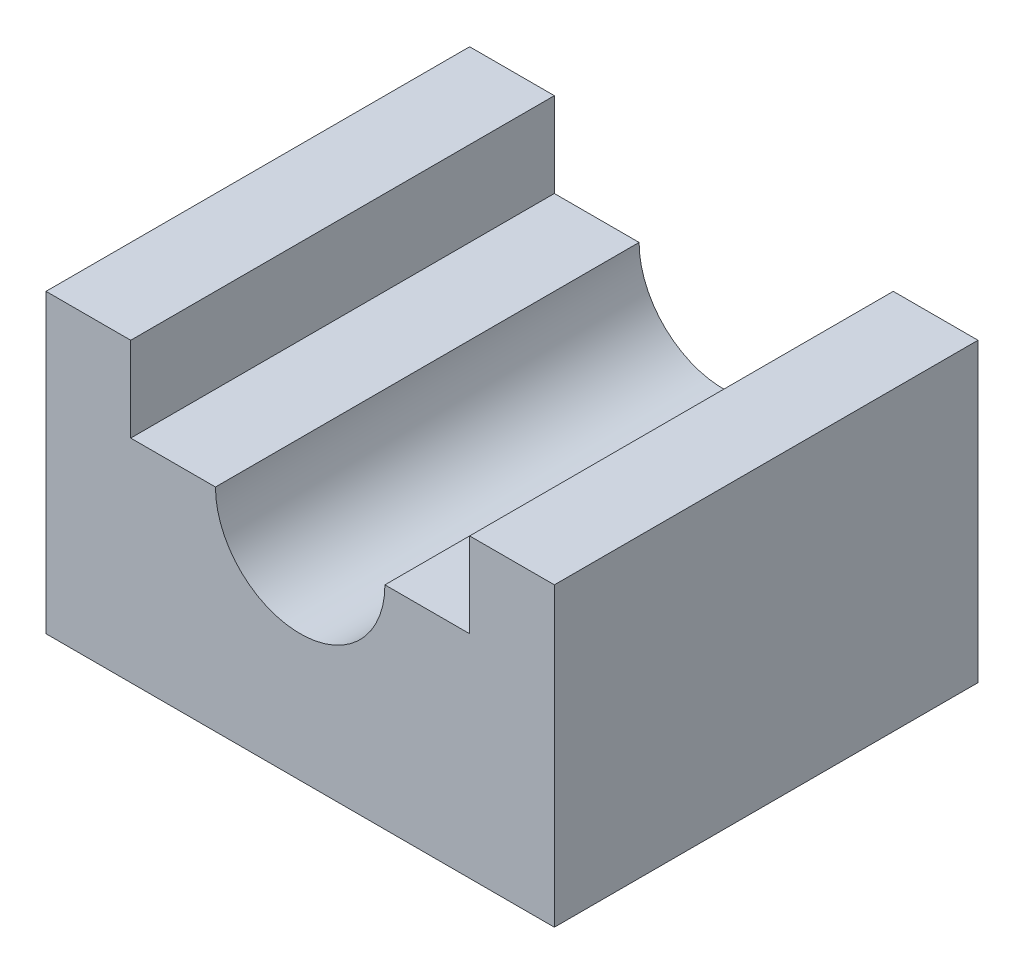
SolidWorks part; units mm, degrees
ref_plane "Front Plane" through (0, 0, 0) normal (0, 0, 1) x (1, 0, 0)
ref_plane "Top Plane" through (0, 0, 0) normal (0, 1, 0) x (1, 0, 0)
ref_plane "Right Plane" through (0, 0, 0) normal (1, 0, 0) x (0, 0, -1)
sketch "Sketch1" plane through (0, 0, 0) normal (0, 0, 1) x (1, 0, 0)
  line L0 (0, 0) -> (25912.0303, 0) construction
  line L1 (0, 0) -> (0, 25912.0303) construction
  line L2 (-20, 35) -> (-20, 25)
  line L3 (-30, 35) -> (-20, 35)
  line L4 (-30, 35) -> (-30, 0)
  line L5 (-30, 0) -> (30, 0)
  line L6 (30, 35) -> (30, 0)
  line L7 (-30, 35) -> (30, 0) construction
  line L8 (-30, 0) -> (30, 35) construction
  line L9 (-20, 25) -> (-10, 25)
  line L10 (10, 25) -> (20, 25)
  line L11 (20, 25) -> (20, 35)
  line L12 (20, 35) -> (30, 35)
  arc A0 (-10, 25) -> (10, 25) centre (0, 25) ccw
  point P5 (0, 17.5)
  dimension "D3" = 10
  dimension "D1" = 60
  dimension "D2" = 35
  dimension "D4" = 20
  dimension "D5" = 10
extrude "Boss-Extrude1" add sketch "Sketch1" along normal blind 50
